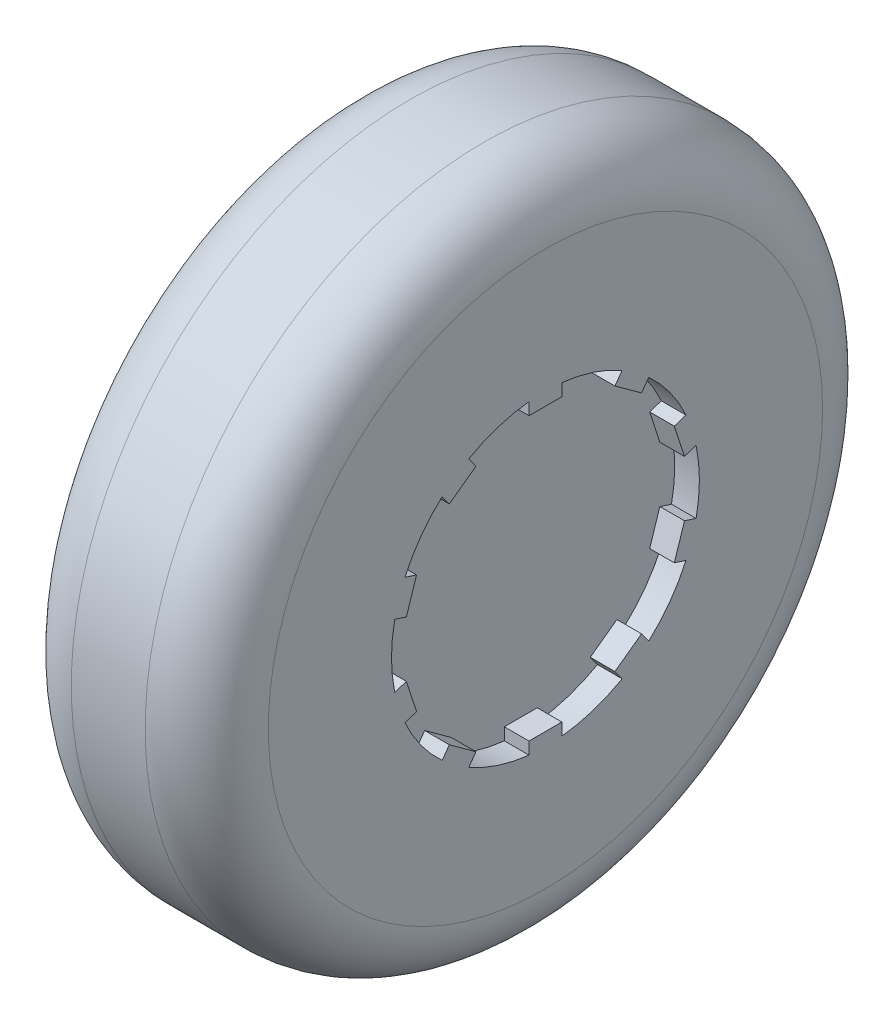
SolidWorks part; units mm, degrees
ref_plane "Front Plane" through (0, 0, 0) normal (0, 0, 1) x (1, 0, 0)
ref_plane "Top Plane" through (0, 0, 0) normal (0, 1, 0) x (1, 0, 0)
ref_plane "Right Plane" through (0, 0, 0) normal (1, 0, 0) x (0, 0, -1)
sketch "Sketch1" plane through (0, 0, 0) normal (1, 0, 0) x (0, 0, -1)
  circle A0 centre (0, 0) radius 275
  dimension "D1" = 550
extrude "Boss-Extrude1" add sketch "Sketch1" along normal blind 160
fillet "Fillet1" radius 50 2 edges at (0, 0, -275) (160, 0, -275)
sketch "Sketch2" plane through (0, 0, 0) normal (-1, 0, 0) x (0, 0, 1)
  circle A0 centre (0, 0) radius 25
  dimension "D1" = 50
extrude "Cut-Extrude1" cut sketch "Sketch2" against normal blind 50
sketch "Sketch3" plane through (160, 0, 0) normal (1, 0, 0) x (0, 0, -1)
  circle A0 centre (0, 0) radius 125
  dimension "D1" = 250
extrude "Cut-Extrude2" cut sketch "Sketch3" against normal blind 20
sketch "Sketch4" plane through (160, 0, 0) normal (1, 0, 0) x (0, 0, -1)
  line L0 (-56.4091, -100.3716) -> (-90.5372, -101.8827) construction
  line L1 (13.361, -114.3587) -> (-13.361, -114.3587)
  line L2 (13.361, -114.3587) -> (13.361, -135.6413)
  line L3 (13.361, -135.6413) -> (-13.361, -135.6413)
  line L4 (-13.361, -114.3587) -> (-13.361, -135.6413)
  line L5 (13.361, -114.3587) -> (-13.361, -135.6413) construction
  line L6 (13.361, -135.6413) -> (-13.361, -114.3587) construction
  line L7 (-68.9186, -117.5895) -> (-78.0277, -84.6648) construction
  line L8 (-56.4091, -100.3716) -> (-68.9186, -117.5895)
  line L9 (-56.4091, -100.3716) -> (-78.0277, -84.6648)
  line L10 (-78.0277, -84.6648) -> (-90.5372, -101.8827)
  line L11 (-68.9186, -117.5895) -> (-90.5372, -101.8827)
  line L12 (-104.6328, -48.0459) -> (-133.1313, -29.2084) construction
  line L13 (-124.8737, -54.6225) -> (-112.8904, -22.6317) construction
  line L14 (-104.6328, -48.0459) -> (-124.8737, -54.6225)
  line L15 (-104.6328, -48.0459) -> (-112.8904, -22.6317)
  line L16 (-112.8904, -22.6317) -> (-133.1313, -29.2084)
  line L17 (-124.8737, -54.6225) -> (-133.1313, -29.2084)
  line L18 (-112.8904, 22.6317) -> (-124.8737, 54.6225) construction
  line L19 (-133.1313, 29.2084) -> (-104.6328, 48.0459) construction
  line L20 (-112.8904, 22.6317) -> (-133.1313, 29.2084)
  line L21 (-112.8904, 22.6317) -> (-104.6328, 48.0459)
  line L22 (-104.6328, 48.0459) -> (-124.8737, 54.6225)
  line L23 (-133.1313, 29.2084) -> (-124.8737, 54.6225)
  line L24 (-78.0277, 84.6648) -> (-68.9186, 117.5895) construction
  line L25 (-90.5372, 101.8827) -> (-56.4091, 100.3716) construction
  line L26 (-78.0277, 84.6648) -> (-90.5372, 101.8827)
  line L27 (-78.0277, 84.6648) -> (-56.4091, 100.3716)
  line L28 (-56.4091, 100.3716) -> (-68.9186, 117.5895)
  line L29 (-90.5372, 101.8827) -> (-68.9186, 117.5895)
  line L30 (-13.361, 114.3587) -> (13.361, 135.6413) construction
  line L31 (-13.361, 135.6413) -> (13.361, 114.3587) construction
  line L32 (-13.361, 114.3587) -> (-13.361, 135.6413)
  line L33 (-13.361, 114.3587) -> (13.361, 114.3587)
  line L34 (13.361, 114.3587) -> (13.361, 135.6413)
  line L35 (-13.361, 135.6413) -> (13.361, 135.6413)
  line L36 (56.4091, 100.3716) -> (90.5372, 101.8827) construction
  line L37 (68.9186, 117.5895) -> (78.0277, 84.6648) construction
  line L38 (56.4091, 100.3716) -> (68.9186, 117.5895)
  line L39 (56.4091, 100.3716) -> (78.0277, 84.6648)
  line L40 (78.0277, 84.6648) -> (90.5372, 101.8827)
  line L41 (68.9186, 117.5895) -> (90.5372, 101.8827)
  line L42 (104.6328, 48.0459) -> (133.1313, 29.2084) construction
  line L43 (124.8737, 54.6225) -> (112.8904, 22.6317) construction
  line L44 (104.6328, 48.0459) -> (124.8737, 54.6225)
  line L45 (104.6328, 48.0459) -> (112.8904, 22.6317)
  line L46 (112.8904, 22.6317) -> (133.1313, 29.2084)
  line L47 (124.8737, 54.6225) -> (133.1313, 29.2084)
  line L48 (112.8904, -22.6317) -> (124.8737, -54.6225) construction
  line L49 (133.1313, -29.2084) -> (104.6328, -48.0459) construction
  line L50 (112.8904, -22.6317) -> (133.1313, -29.2084)
  line L51 (112.8904, -22.6317) -> (104.6328, -48.0459)
  line L52 (104.6328, -48.0459) -> (124.8737, -54.6225)
  line L53 (133.1313, -29.2084) -> (124.8737, -54.6225)
  line L54 (78.0277, -84.6648) -> (68.9186, -117.5895) construction
  line L55 (90.5372, -101.8827) -> (56.4091, -100.3716) construction
  line L56 (78.0277, -84.6648) -> (90.5372, -101.8827)
  line L57 (78.0277, -84.6648) -> (56.4091, -100.3716)
  line L58 (56.4091, -100.3716) -> (68.9186, -117.5895)
  line L59 (90.5372, -101.8827) -> (68.9186, -117.5895)
  circle A0 centre (0, 0) radius 125 construction
  circle A1 centre (0, 0) radius 125 construction
  point P0 (0, -125)
  point P11 (-73.4732, -101.1271)
  point P16 (-118.8821, -38.6271)
  point P21 (-118.8821, 38.6271)
  point P26 (-73.4732, 101.1271)
  point P31 (0, 125)
  point P36 (73.4732, 101.1271)
  point P41 (118.8821, 38.6271)
  point P46 (118.8821, -38.6271)
  point P51 (73.4732, -101.1271)
  point P56 (0, 0)
  dimension "D1" = 10
extrude "Boss-Extrude2" add sketch "Sketch4" against normal blind 77
